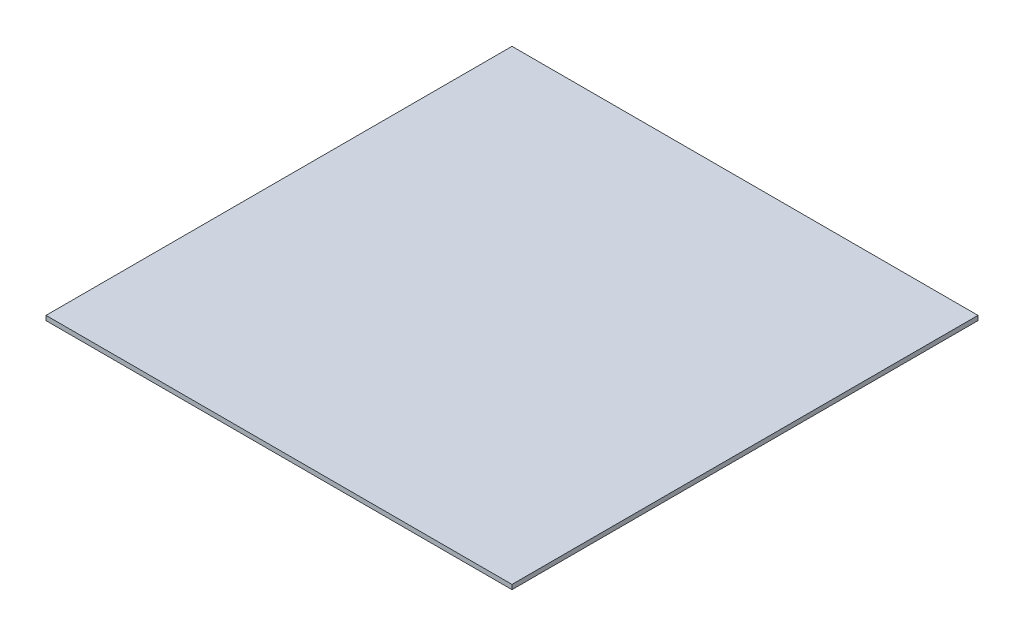
SolidWorks part; units mm, degrees
material "ABS"
ref_plane "Front Plane" through (0, 0, 0) normal (0, 0, 1) x (1, 0, 0)
ref_plane "Top Plane" through (0, 0, 0) normal (0, 1, 0) x (1, 0, 0)
ref_plane "Right Plane" through (0, 0, 0) normal (1, 0, 0) x (0, 0, -1)
sketch "Sketch1" plane through (0, 0, 0) normal (0, 1, 0) x (1, 0, 0)
  line L1 (-152.4, -152.4) -> (152.4, -152.4)
  line L2 (-152.4, -152.4) -> (-152.4, 152.4)
  line L3 (-152.4, 152.4) -> (152.4, 152.4)
  line L4 (152.4, -152.4) -> (152.4, 152.4)
  line L5 (-152.4, -152.4) -> (152.4, 152.4) construction
  line L6 (-152.4, 152.4) -> (152.4, -152.4) construction
  point P0 (0, 0)
  dimension "D1" = 304.8
  dimension "D2" = 304.8
extrude "Boss-Extrude1" add sketch "Sketch1" along normal blind 2.9972
